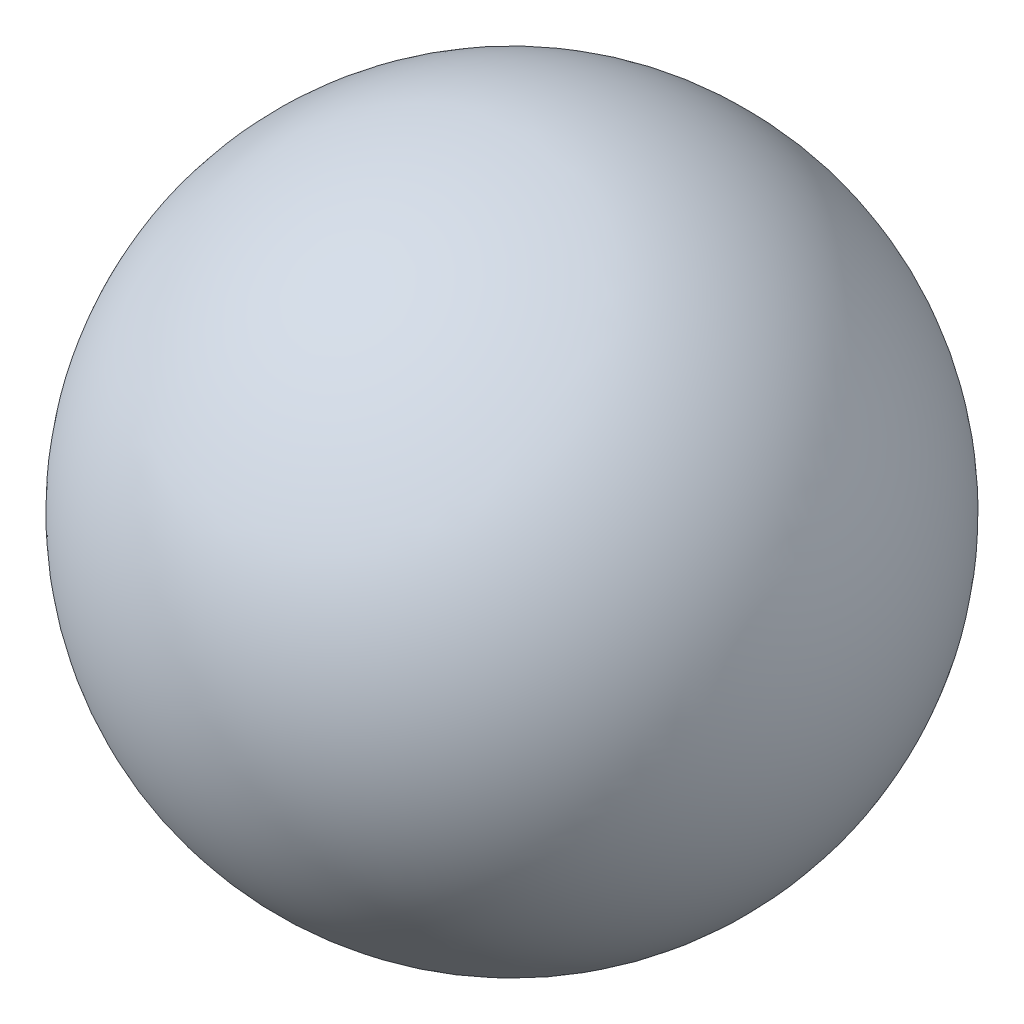
SolidWorks part; units mm, degrees
ref_plane "前视基准面" through (0, 0, 0) normal (0, 0, 1) x (1, 0, 0)
ref_plane "上视基准面" through (0, 0, 0) normal (0, 1, 0) x (1, 0, 0)
ref_plane "右视基准面" through (0, 0, 0) normal (1, 0, 0) x (0, 0, -1)
sketch "草图2" plane through (0, 0, 0) normal (0, 0, 1) x (1, 0, 0)
  line L0 (-0.794, 0) -> (0.794, 0)
  arc A0 (-0.794, 0) -> (0.794, 0) centre (0, 0) ccw
  dimension "D1" = 0.794
revolve "旋转1" add sketch "草图2" angle 360 about L0
